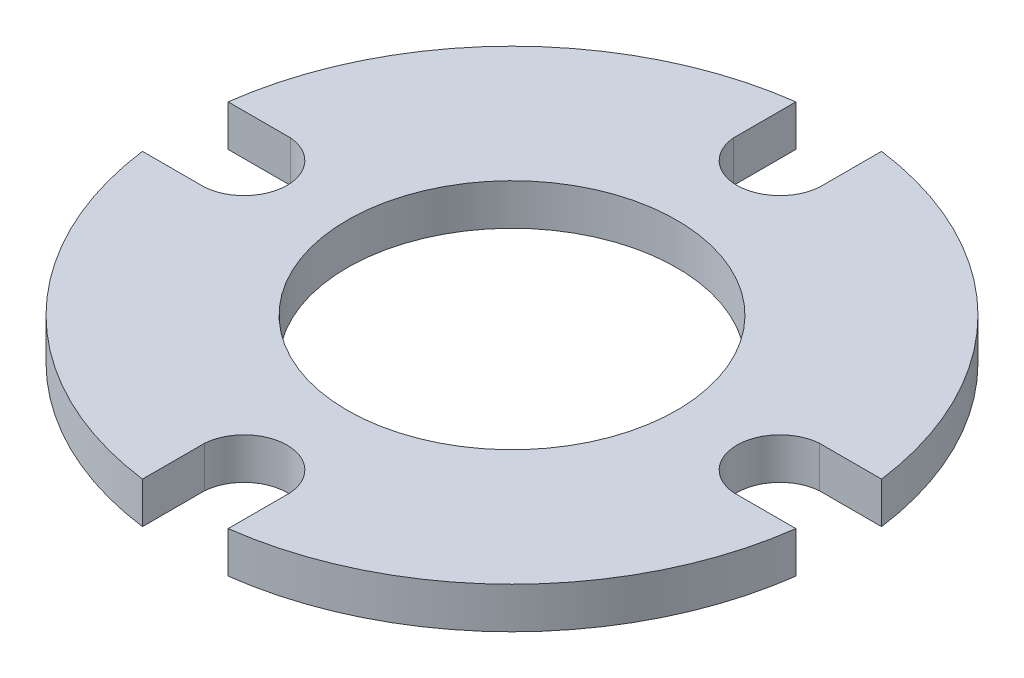
SolidWorks part; units mm, degrees
ref_plane "Front Plane" through (0, 0, 0) normal (0, 0, 1) x (1, 0, 0)
ref_plane "Top Plane" through (0, 0, 0) normal (0, 1, 0) x (1, 0, 0)
ref_plane "Right Plane" through (0, 0, 0) normal (1, 0, 0) x (0, 0, -1)
sketch "Sketch1" plane through (0, 0, 0) normal (0, 1, 0) x (1, 0, 0)
  line L0 (0, 1) -> (0, -1.0339) construction
  line L1 (-1, 0) -> (0.813, 0) construction
  line L2 (0.13, 0.9915) -> (0.13, 0.8025)
  line L3 (-0.13, 0.9915) -> (-0.13, 0.8025)
  line L4 (0.9915, -0.13) -> (0.8025, -0.13)
  line L5 (0.9915, 0.13) -> (0.8025, 0.13)
  line L6 (-0.13, -0.9915) -> (-0.13, -0.8025)
  line L7 (0.13, -0.9915) -> (0.13, -0.8025)
  line L8 (-0.9915, 0.13) -> (-0.8025, 0.13)
  line L9 (-0.9915, -0.13) -> (-0.8025, -0.13)
  arc A0 (-0.13, 0.9915) -> (-0.9915, 0.13) centre (0, 0) ccw
  circle A1 centre (0, 0) radius 0.813 construction
  circle A2 centre (0, 0) radius 0.5
  arc A3 (-0.13, 0.8025) -> (0.13, 0.8025) centre (0, 0.813) ccw
  arc A4 (0.8025, 0.13) -> (0.8025, -0.13) centre (0.813, 0) ccw
  arc A5 (0.13, -0.8025) -> (-0.13, -0.8025) centre (0, -0.813) ccw
  arc A6 (-0.8025, -0.13) -> (-0.8025, 0.13) centre (-0.813, 0) ccw
  arc A7 (-0.9915, -0.13) -> (-0.13, -0.9915) centre (0, 0) ccw
  arc A8 (0.13, -0.9915) -> (0.9915, -0.13) centre (0, 0) ccw
  arc A9 (0.9915, 0.13) -> (0.13, 0.9915) centre (0, 0) ccw
  point P32 (0, 0)
  dimension "D1" = 2
  dimension "D2" = 1
  dimension "D3" = 1.626
  dimension "D5" = 4
  dimension "D4" = 0.13
extrude "Boss-Extrude1" add sketch "Sketch1" along normal blind 0.125
